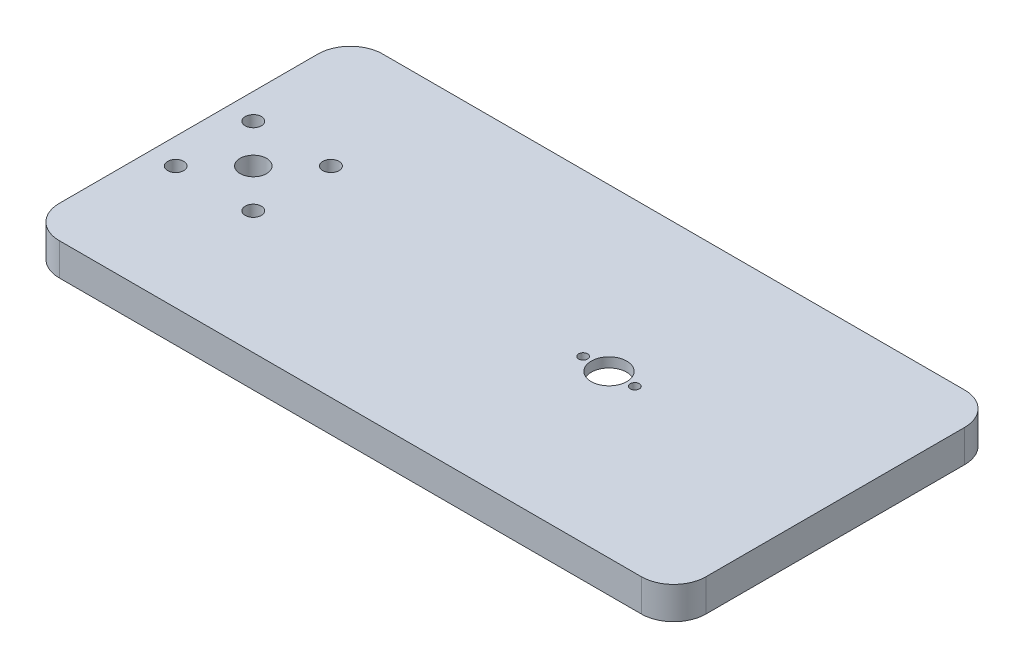
SolidWorks part; units mm, degrees
ref_plane "正面" through (0, 0, 0) normal (0, 0, 1) x (1, 0, 0)
ref_plane "平面" through (0, 0, 0) normal (0, 1, 0) x (1, 0, 0)
ref_plane "右側面" through (0, 0, 0) normal (1, 0, 0) x (0, 0, -1)
sketch "ｽｹｯﾁ1" plane through (0, 0, 0) normal (0, 1, 0) x (1, 0, 0)
  line L1 (-100, -50) -> (100, -50)
  line L2 (-100, -50) -> (-100, 50)
  line L3 (-100, 50) -> (100, 50)
  line L4 (100, -50) -> (100, 50)
  line L5 (-100, -50) -> (100, 50) construction
  line L6 (-100, 50) -> (100, -50) construction
  point P0 (0, 0)
  dimension "D1" = 200
  dimension "D2" = 100
extrude "ﾎﾞｽ - 押し出し1" add sketch "ｽｹｯﾁ1" along normal blind 10
sketch "ｽｹｯﾁ2" plane through (0, 10, 0) normal (0, 1, 0) x (1, 0, 0)
  line L0 (30, 0) -> (-80, 0) construction
  line L1 (-100, 50) -> (-100, -50) construction
  circle A0 centre (-92, 12) radius 2.5
  circle A1 centre (-68, 12) radius 2.5
  circle A2 centre (-92, -12) radius 2.5
  circle A3 centre (-68, -12) radius 2.5
  circle A4 centre (30, 0) radius 5.5
  circle A5 centre (38, 0) radius 1.4
  circle A6 centre (22, 0) radius 1.4
  circle A7 centre (-80, 0) radius 4.1
  dimension "D3" = 5
  dimension "D8" = 11
  dimension "D9" = 2.8
  dimension "D12" = 8.2
  dimension "D1" = 110
  dimension "D2" = 20
  dimension "D4" = 24
  dimension "D5" = 24
  dimension "D6" = 12
  dimension "D7" = 12
  dimension "D10" = 16
  dimension "D11" = 8
extrude "ｶｯﾄ - 押し出し1" cut sketch "ｽｹｯﾁ2" against normal through all
sketch "ｽｹｯﾁ3" plane through (0, 0, 0) normal (0, -1, 0) x (1, 0, 0)
  circle A0 centre (30, 0) radius 16
  dimension "D1" = 32
extrude "ｶｯﾄ - 押し出し2" cut sketch "ｽｹｯﾁ3" against normal offset from surface (7 mm away) 3 up to face at (38, 10, 1.4)
sketch "ｽｹｯﾁ4" plane through (0, 0, 0) normal (0, -1, 0) x (1, 0, 0)
  line L21 (-100, 50) -> (100, 50) construction
  line L22 (-100, -50) -> (-100, 50) construction
  line L23 (100, 50) -> (100, -50) construction
  line L24 (100, -50) -> (-100, -50) construction
  circle A0 centre (-85, 35) radius 5.1
  circle A1 centre (-85, -35) radius 5.1
  circle A2 centre (85, -35) radius 5.1
  circle A3 centre (85, 35) radius 5.1
  dimension "D1" = 10.2
  dimension "D2" = 15
  dimension "D3" = 15
  dimension "D4" = 15
  dimension "D5" = 15
fillet "ﾌｨﾚｯﾄ1" radius 10 4 edges at (100, 5, -50) (-100, 5, -50) (100, 5, 50) (-100, 5, 50)
extrude "ｶｯﾄ - 押し出し4" cut sketch "ｽｹｯﾁ4" against normal blind 5
